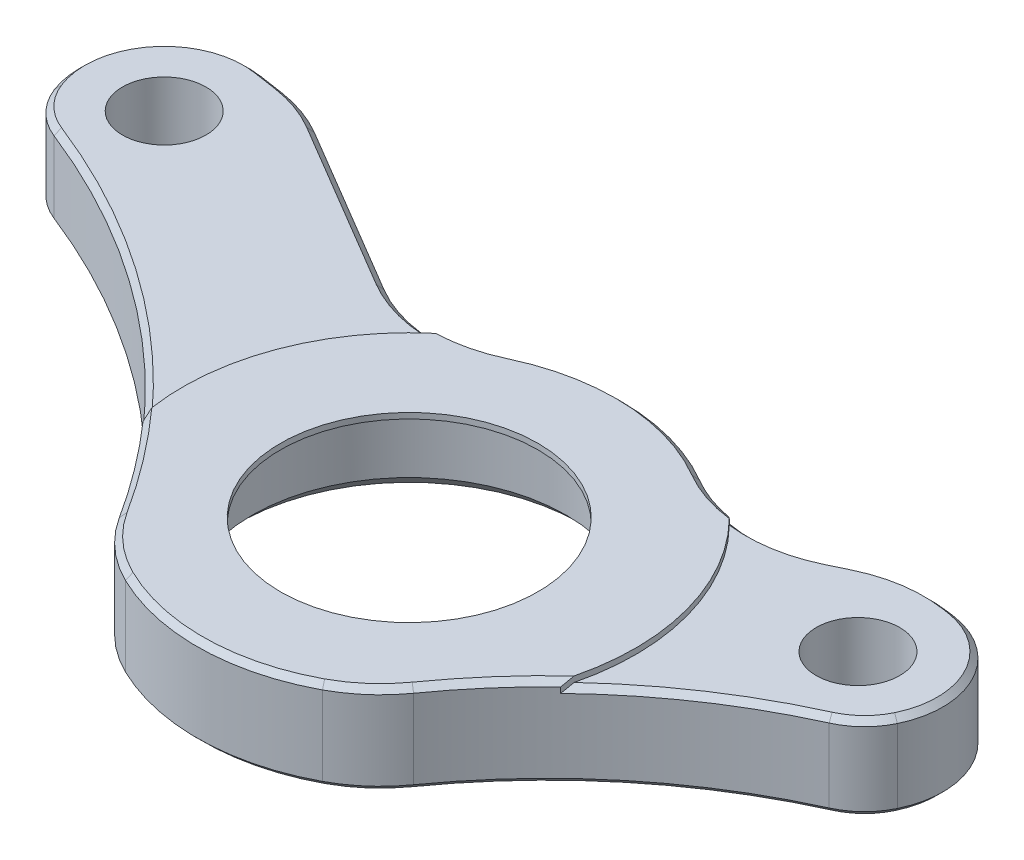
SolidWorks part; units mm, degrees
ref_plane "Front Plane" through (0, 0, 0) normal (0, 0, 1) x (1, 0, 0)
ref_plane "Top Plane" through (0, 0, 0) normal (0, 1, 0) x (1, 0, 0)
ref_plane "Right Plane" through (0, 0, 0) normal (1, 0, 0) x (0, 0, -1)
sketch "Sketch1" plane through (0, 0, 0) normal (0, 1, 0) x (1, 0, 0)
  line L0 (-9.6218, -11.5074) -> (-37.9445, 12.1742)
  line L1 (-33.2001, 22.71) -> (24.5619, 13.9894)
  line L2 (27.5149, 3.4537) -> (9.6218, -11.5074)
  line L3 (-34.0958, 16.7772) -> (0, 0) construction
  line L4 (0, 0) -> (23.6662, 8.0567) construction
  line L5 (23.6662, 8.0567) -> (-34.0958, 16.7772) construction
  circle A0 centre (0, 0) radius 11.1
  arc A1 (-9.6218, -11.5074) -> (9.6218, -11.5074) centre (0, 0) ccw
  arc A2 (24.5619, 13.9894) -> (27.5149, 3.4537) centre (23.6662, 8.0567) cw
  arc A3 (-37.9445, 12.1742) -> (-33.2001, 22.71) centre (-34.0958, 16.7772) cw
  circle A4 centre (-34.0958, 16.7772) radius 2.95
  circle A5 centre (23.6662, 8.0567) radius 2.95
  dimension "D1" = 22.2
  dimension "D2" = 15
  dimension "D3" = 6
  dimension "D4" = 38
  dimension "D6" = 5.9
  dimension "D8" = 5.9
  dimension "D5" = 135
  dimension "D7" = 25
extrude "Boss-Extrude1" add sketch "Sketch1" along normal blind 6.4
sketch "Sketch6" plane through (0, 6.4, 0) normal (0, 1, 0) x (1, 0, 0)
  line L0 (-10.3975, 10.8116) -> (-29.543, 22.1578)
  line L1 (24.5619, 13.9894) -> (-33.2001, 22.71) construction
  line L2 (11.3133, 9.8493) -> (21.0661, 14.5172)
  line L3 (-29.543, 22.1578) -> (21.0661, 14.5172)
  line L4 (-32.5918, 19.315) -> (-12.4369, 7.3705) construction
  line L5 (-12.4369, 7.3705) -> (-10.3975, 10.8116) construction
  line L6 (-12.4369, 7.3705) -> (0, 0) construction
  line L7 (22.3927, 10.7176) -> (0, 0) construction
  line L8 (11.3133, 9.8493) -> (13.0402, 6.2413) construction
  arc A1 (-10.3975, 10.8116) -> (11.3133, 9.8493) centre (0, 0) cw
  circle A2 centre (-34.0958, 16.7772) radius 2.95 construction
  circle A3 centre (23.6662, 8.0567) radius 2.95 construction
  dimension "D1" = 15
  dimension "D2" = 4
  dimension "D3" = 4
extrude "Cut-Extrude4" cut sketch "Sketch6" against normal up to next
chamfer "Chamfer1" distance 1 angle 45 1 edges at (0, 6.4, 11.1)
sketch "Sketch5" plane through (0, 6.4, 0) normal (0, 1, 0) x (1, 0, 0)
  line L1 (-37.9445, 12.1742) -> (-9.6218, -11.5074) construction
  line L2 (-37.9445, 12.1742) -> (-9.6218, -11.5074)
  line L4 (9.6218, -11.5074) -> (27.5149, 3.4537) construction
  line L5 (9.6218, -11.5074) -> (27.5149, 3.4537)
  arc A0 (-37.9445, 12.1742) -> (-9.6218, -11.5074) centre (-57.0167, -39.4131) cw
  arc A1 (27.5149, 3.4537) -> (9.6218, -11.5074) centre (43.1118, -33.3803) ccw
  dimension "D1" = 55
  dimension "D2" = 40
extrude "Cut-Extrude3" cut sketch "Sketch5" against normal through all
fillet "Fillet1" radius 10 6 edges at (9.6218, 3.2, 11.5074) (-9.6218, 3.2, 11.5074) (21.0661, 3.2, -14.5172) (11.3133, 3.2, -9.8493) (-10.3975, 3.2, -10.8116) (-29.543, 3.2, -22.1578)
fillet "Fillet2" radius 5 2 edges at (27.5149, 3.2, -3.4537) (-37.9445, 3.2, -12.1742)
sketch "Sketch7" plane through (0, 0, 0) normal (0, -1, 0) x (1, 0, 0)
  circle A0 centre (0, 0) radius 11.1 construction
  circle A1 centre (0, 0) radius 11.1
  circle A4 centre (0, 0) radius 9.1
  circle A5 centre (0, 0) radius 9.1
  dimension "D1" = 2
extrude "Boss-Extrude2" add sketch "Sketch7" against normal blind 0.4
sketch "Sketch9" plane through (0, 0, 0) normal (0, -1, 0) x (1, 0, 0)
  circle A0 centre (0, 0) radius 16
  dimension "D1" = 32
extrude "Cut-Extrude5" cut sketch "Sketch9" against normal blind 0.4 flip side to cut
sketch "Sketch10" plane through (0, 0.4, 0) normal (0, -1, 0) x (1, 0, 0)
  line L2 (-33.2001, -22.71) -> (-31.471, -22.4489)
  line L3 (-27.8655, -21.1637) -> (-15.779, -14.0008)
  line L4 (-33.2001, -22.71) -> (-31.471, -22.4489)
  line L5 (-27.8655, -21.1637) -> (-15.779, -14.0008)
  arc A6 (-9.8074, -12.6418) -> (-15.779, -14.0008) centre (-10.6807, -22.6036) ccw
  arc A7 (-15.6934, 3.1173) -> (-9.8074, -12.6418) centre (0, 0) ccw
  arc A8 (-36.8592, -11.7599) -> (-15.6934, 3.1173) centre (-57.0167, 39.4131) ccw
  arc A9 (-36.8592, -11.7599) -> (-39.6814, -14.586) centre (-35.0268, -16.412) ccw
  arc A10 (-39.6814, -14.586) -> (-33.2001, -22.71) centre (-34.0958, -16.7772) ccw
  arc A11 (-31.471, -22.4489) -> (-27.8655, -21.1637) centre (-32.9638, -12.561) ccw
  arc A12 (-9.8074, -12.6418) -> (-15.779, -14.0008) centre (-10.6807, -22.6036) ccw
  arc A13 (-15.6934, 3.1173) -> (-9.8074, -12.6418) centre (0, 0) ccw
  arc A14 (-36.8592, -11.7599) -> (-15.6934, 3.1173) centre (-57.0167, 39.4131) ccw
  arc A15 (-36.8592, -11.7599) -> (-39.6814, -14.586) centre (-35.0268, -16.412) ccw
  arc A16 (-39.6814, -14.586) -> (-33.2001, -22.71) centre (-34.0958, -16.7772) ccw
  arc A17 (-31.471, -22.4489) -> (-27.8655, -21.1637) centre (-32.9638, -12.561) ccw
  dimension "D1" = 0
extrude "Cut-Extrude6" cut sketch "Sketch10" against normal blind 0.15
chamfer "Chamfer2" distance 0.4 angle 45 40 edges at (9.1813, 0, -12.1867) (0.6642, 0, -14.9853) (-8.0671, 0, -12.9512) (12.7875, 0, 7.2951) (8.9736, 0, 11.9094) (0.2843, 0, 14.9973) (-8.8535, 0, 11.9526) (-13.0309, 0, 6.3941) (-8.8535, 6.4, 11.9526) (0.2843, 6.4, 14.9973) (-22.0306, 6.4, -3.0248) (8.9736, 6.4, 11.9094) (-38.5647, 6.4, -12.8789) (17.6887, 6.4, 2.4987) (-38.7861, 6.4, -20.5191) (28.0543, 6.4, -4.0382) (-32.3356, 6.4, -22.5795) (28.9749, 6.4, -10.8527) (-29.6062, 6.4, -21.9804) (24.3332, 6.4, -14.024) (-21.8223, 6.4, -17.5823) (21.1343, 6.4, -14.0608) (-11.1483, 6.4, -12.6145) (17.6251, 6.4, -12.8703) (0.6642, 6.4, -14.9853) (12.2207, 6.4, -11.5788) (13.9863, 0.4, -11.6612) (17.6251, 0.4, -12.8703) (21.1343, 0.4, -14.0608) (20.6438, 0.4, 0.2866) (24.3332, 0.4, -14.024) (28.0543, 0.4, -4.0382) (28.9749, 0.4, -10.8527) (-25.3891, 0.55, -5.5835) (-38.5647, 0.55, -12.8789) (-38.7861, 0.55, -20.5191) (-32.3356, 0.55, -22.5795) (-29.6062, 0.55, -21.9804) (-12.8998, 0.55, -12.8529) (-21.8223, 0.55, -17.5823)
mirror "Mirror1" about plane through (0, 0, 0) normal (0, 1, 0) of bodies 113 106
delete or keep bodies "Body-Delete/Keep 1" type delete bodies bodies 113
